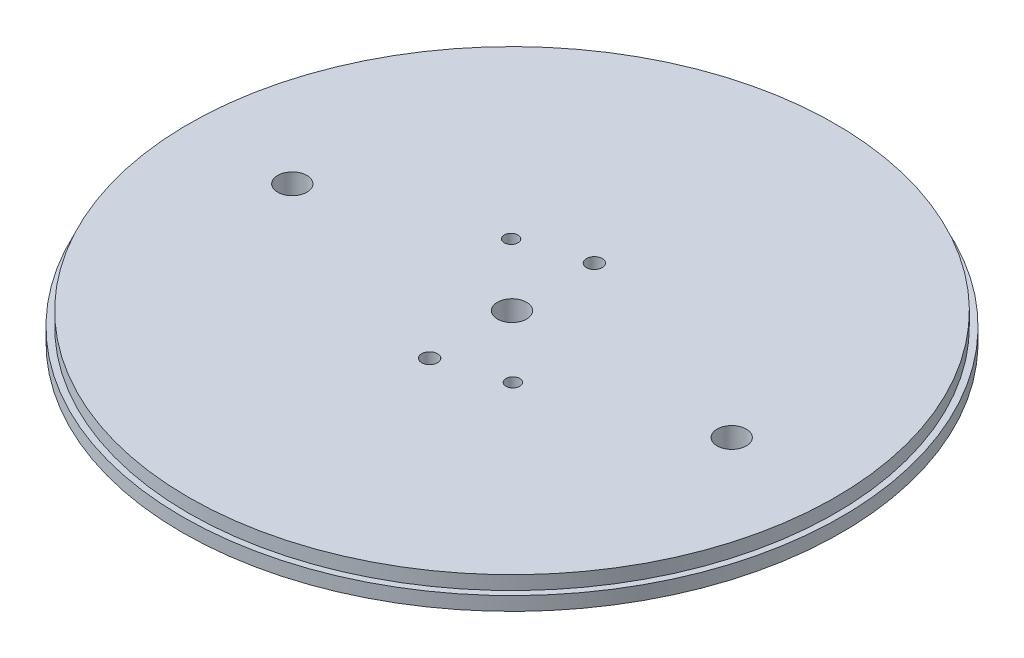
SolidWorks part; units mm, degrees
ref_plane "Front Plane" through (0, 0, 0) normal (0, 0, 1) x (1, 0, 0)
ref_plane "Top Plane" through (0, 0, 0) normal (0, 1, 0) x (1, 0, 0)
ref_plane "Right Plane" through (0, 0, 0) normal (1, 0, 0) x (0, 0, -1)
sketch "Sketch1" plane through (0, 0, 0) normal (0, 1, 0) x (1, 0, 0)
  circle A0 centre (0, 0) radius 76.2
  dimension "D1" = 152.4
extrude "Boss-Extrude1" add sketch "Sketch1" along normal mid plane 3.175
sketch "Sketch2" plane through (0, 1.5875, 0) normal (0, 1, 0) x (1, 0, 0)
  circle A0 centre (0, 0) radius 74.7776
  dimension "D1" = 149.5552
extrude "Boss-Extrude2" add sketch "Sketch2" along normal blind 3.175
sketch "Sketch3" plane through (0, -1.5875, 0) normal (0, -1, 0) x (1, 0, 0)
  circle A0 centre (50.8, 0) radius 3.3782 construction
  circle A1 centre (-50.8, 0) radius 3.3782 construction
  circle A2 centre (50.8, 0) radius 3.3782
  circle A3 centre (-50.8, 0) radius 3.3782
  circle A4 centre (0, 0) radius 3.3782
  dimension "D1" = 6.7564
extrude "Cut-Extrude1" cut sketch "Sketch3" against normal through all
hole_wizard "#27 (0.144) Diameter Hole1" positions "Sketch8" profile "Sketch9" hole size "#27" standard "ANSI Inch" end condition through all
sketch "Sketch8" plane through (0, -1.5875, 0) normal (0, -1, 0) x (-1, 0, 0)
  line L0 (0, 19.05) -> (0, -19.05) construction
  point P0 (0, 19.05)
  point P2 (0, -19.05)
  point P9 (0, 0)
  dimension "D1" = 38.1
sketch "Sketch9" plane through (0, -1.5875, -19.05) normal (1, 0, 0) x (0, 0, -1)
  line L0 (0, 0) -> (0, 6.35)
  line L1 (0, 6.35) -> (1.8288, 6.35)
  line L2 (1.8288, 6.35) -> (1.8288, 0)
  line L5 (1.8288, 0) -> (0, 0)
  line L11 (0, -6.35) -> (0, 107.95) construction
  dimension "Thru Hole Dia." = 3.6576
  dimension "Thru Hole Depth" = 6.35
hole_wizard "1/8 (0.125) Diameter Hole1" positions "Sketch10" profile "Sketch11" hole size "1/8" standard "ANSI Inch" end condition through all
sketch "Sketch10" plane through (0, -1.5875, 0) normal (0, -1, 0) x (-1, 0, 0)
  line L0 (-14.4698, -14.2663) -> (14.4698, 14.2663) construction
  circle A0 centre (0, 19.05) radius 1.8288 construction
  point P0 (14.4698, 14.2663)
  point P2 (-14.4698, -14.2663)
  point P8 (0, 0)
  dimension "D1" = 40.64
  dimension "D2" = 15.24
sketch "Sketch11" plane through (-14.4698, -1.5875, -14.2663) normal (1, 0, 0) x (0, 0, -1)
  line L0 (0, 0) -> (0, 6.35)
  line L1 (0, 6.35) -> (1.5875, 6.35)
  line L2 (1.5875, 6.35) -> (1.5875, 0)
  line L5 (1.5875, 0) -> (0, 0)
  line L11 (0, -6.35) -> (0, 107.95) construction
  dimension "Thru Hole Dia." = 3.175
  dimension "Thru Hole Depth" = 6.35
